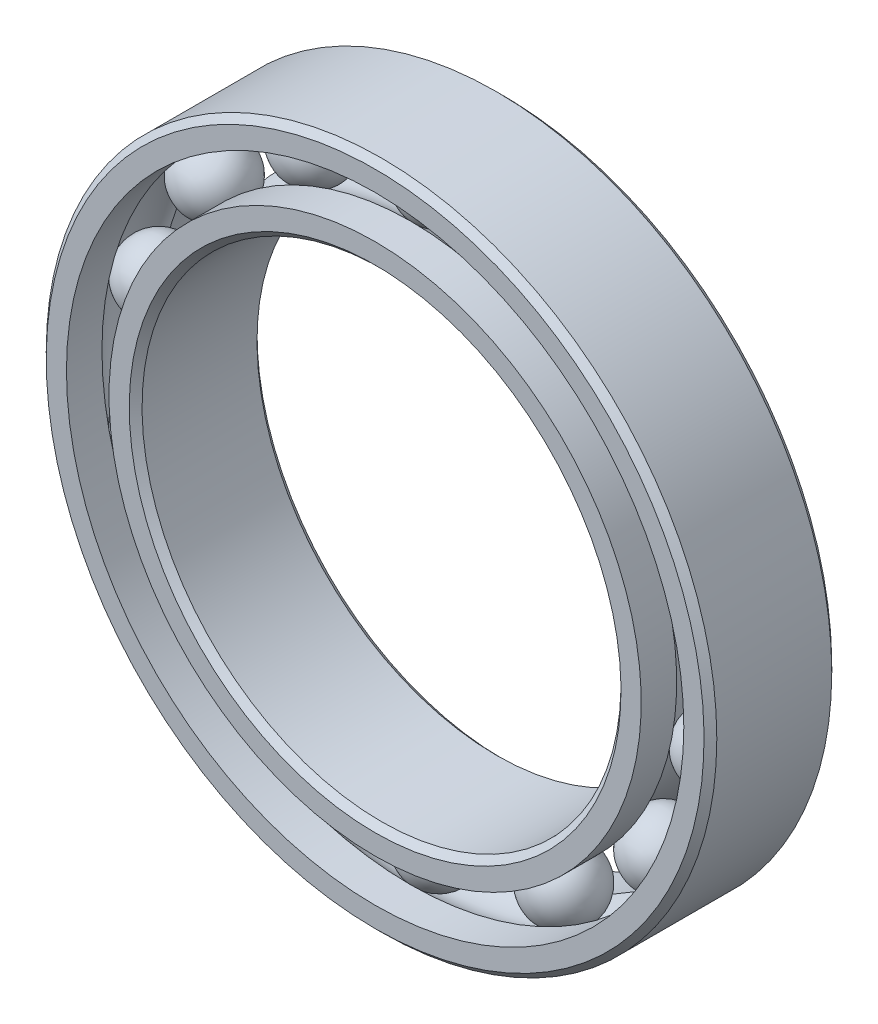
SolidWorks part; units mm, degrees
ref_plane "Front Plane" through (0, 0, 0) normal (0, 0, 1) x (1, 0, 0)
ref_plane "Top Plane" through (0, 0, 0) normal (0, 1, 0) x (1, 0, 0)
ref_plane "Right Plane" through (0, 0, 0) normal (1, 0, 0) x (0, 0, -1)
sketch "Sketch1" plane through (0, 0, 0) normal (0, 0, 1) x (1, 0, 0)
  circle A0 centre (0, 0) radius 10.5
  circle A1 centre (0, 0) radius 7.5
  dimension "OD" = 21
  dimension "ID" = 15
  dimension "For Shaft Diameter" = 15
  dimension "For Housing ID" = 21
sketch "Sketch5" plane through (0, 0, 0) normal (1, 0, 0) x (0, 0, -1)
  line L0 (-2, 0) -> (2, 0) construction
  line L1 (0, 10.5) -> (0, -10.5) construction
  line L2 (1.8, 10.5) -> (-1.8, 10.5)
  line L3 (-1.8, 10.5) -> (-2, 10.3)
  line L4 (-2, 10.3) -> (-2, 9.6667)
  line L5 (-2, 9.6667) -> (-0.8889, 9.6667)
  line L6 (2, 9.6667) -> (0.8889, 9.6667)
  line L7 (2, 10.3) -> (2, 9.6667)
  line L8 (1.8, 10.5) -> (2, 10.3)
  line L9 (0, 10.5) -> (0, 9) construction
  line L10 (0, 9) -> (0, 7.5) construction
  line L11 (-1.1111, 9) -> (-2, 9) construction
  line L12 (1.3651, 8.3587) -> (1.7461, 8.3587) construction
  line L13 (-1.3651, 8.3587) -> (-1.7461, 8.3587) construction
  line L14 (-1.3651, 8.3587) -> (-1.3651, 9.6413) construction
  line L15 (-1.3651, 9.6413) -> (-1.7461, 9.6413) construction
  line L16 (-1.7461, 8.3587) -> (-1.7461, 9.6413) construction
  line L17 (-1.3651, 8.3587) -> (-1.7461, 9.6413) construction
  line L18 (-1.3651, 9.6413) -> (-1.7461, 8.3587) construction
  line L19 (1.7461, 8.3587) -> (1.7461, 9.6413) construction
  line L20 (1.3651, 9.6413) -> (1.7461, 9.6413) construction
  line L21 (1.3651, 8.3587) -> (1.3651, 9.6413) construction
  line L22 (0, 10.5) -> (0, -10.5) construction
  arc A0 (-0.8889, 9.6667) -> (0.8889, 9.6667) centre (0, 9) cw
  circle A1 centre (0, 9) radius 1.1111 construction
  point P14 (0, 7.5)
  point P15 (-1.5556, 9)
  dimension "D1" = 45
  dimension "D2" = 0.2
  dimension "D3" = 1.7778
  dimension "D4" = 0.6667
  dimension "D5" = 0.381
  dimension "D6" = 0.0254
  dimension "Width" = 4
sketch "Sketch6" plane through (0, 0, 0) normal (1, 0, 0) x (0, 0, -1)
  line L0 (1.8, 10.5) -> (2, 10.3) construction
  line L1 (2, 10.3) -> (2, 9.6667) construction
  line L2 (2, 9.6667) -> (0.8889, 9.6667) construction
  line L3 (-2, 9.6667) -> (-0.8889, 9.6667) construction
  line L4 (-2, 10.3) -> (-2, 9.6667) construction
  line L5 (-1.8, 10.5) -> (-2, 10.3) construction
  line L6 (1.8, 10.5) -> (-1.8, 10.5) construction
  line L7 (1.8, 10.5) -> (2, 10.3)
  line L8 (2, 10.3) -> (2, 9.6667)
  line L9 (2, 9.6667) -> (0.8889, 9.6667)
  line L10 (-2, 9.6667) -> (-0.8889, 9.6667)
  line L11 (-2, 10.3) -> (-2, 9.6667)
  line L12 (-1.8, 10.5) -> (-2, 10.3)
  line L13 (1.8, 10.5) -> (-1.8, 10.5)
  arc A0 (0.8889, 9.6667) -> (-0.8889, 9.6667) centre (0, 9) ccw construction
  arc A1 (0.8889, 9.6667) -> (-0.8889, 9.6667) centre (0, 9) ccw
revolve "Revolve5" add sketch "Sketch6" angle 360 about L0
sketch "Sketch3" plane through (0, 0, 0) normal (1, 0, 0) x (0, 0, -1)
  line L0 (-2, 8.3333) -> (-0.8889, 8.3333)
  line L1 (0, 10.5) -> (0, -10.5) construction
  line L2 (-2, 10.3) -> (-2, 9.6667) construction
  line L3 (-2, 8.3333) -> (-2, 7.7)
  line L4 (-1.8, 10.5) -> (-2, 10.3) construction
  line L5 (-2, 7.7) -> (-1.8, 7.5)
  line L6 (-1.8, 7.5) -> (1.8, 7.5)
  line L8 (1.8, 7.5) -> (2, 7.7)
  line L10 (2, 7.7) -> (2, 8.3333)
  line L11 (2, 8.3333) -> (0.8889, 8.3333)
  line L12 (1.8, 10.5) -> (1.8, -10.5) construction
  line L13 (1.8, 10.5) -> (2, 10.3) construction
  line L14 (2, -10.3) -> (2, 10.3) construction
  arc A0 (0.8889, 9.6667) -> (-0.8889, 9.6667) centre (0, 9) ccw construction
  arc A1 (0.8889, 8.3333) -> (-0.8889, 8.3333) centre (0, 9) cw
revolve "Revolve3" add sketch "Sketch3" angle 360 about L0
sketch "Sketch4" plane through (0, 0, 0) normal (1, 0, 0) x (0, 0, -1)
  line L0 (-1.1111, 9) -> (1.1111, 9)
  arc A2 (-1.1111, 9) -> (1.1111, 9) centre (0, 9) cw
  arc A3 (0.8889, 9.6667) -> (-0.8889, 9.6667) centre (0, 9) ccw construction
revolve "Revolve4" add sketch "Sketch4" angle 360 about L0
pattern_circular "CirPattern1" count 14 over 360 about axis through (0, 0, 0) along (0, 0, 1) of bodies 104
equation "\"D2@Sketch5\" = \"Width@Sketch5\" * .05"
equation "\"D3@Sketch5\" = \"Width@Sketch5\" / 2.25"
equation "\"D4@Sketch5\"=((\"OD@Sketch1\"-\"ID@Sketch1\")/2)/4.5"
